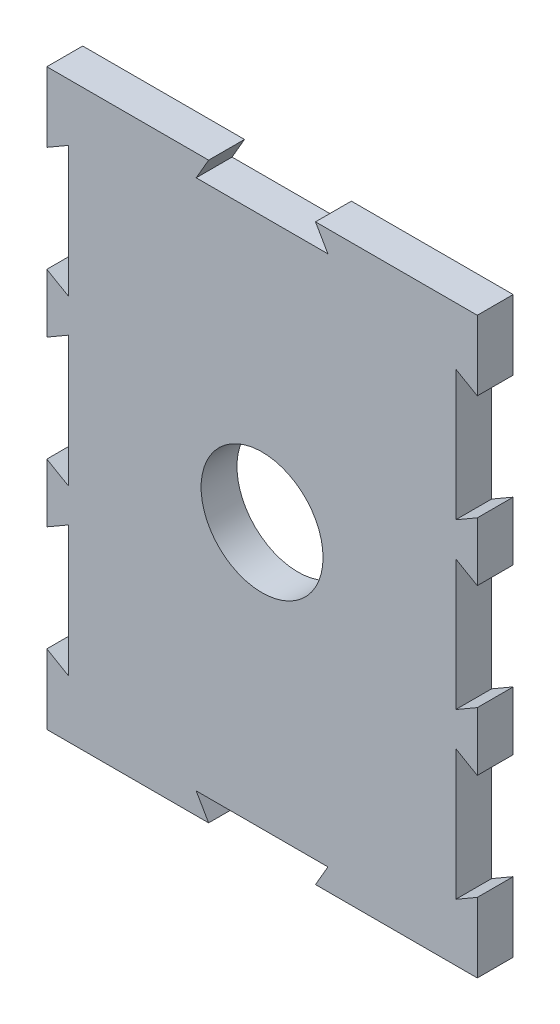
SolidWorks part; units mm, degrees
ref_plane "Front Plane" through (0, 0, 0) normal (1, 0, 0) x (0, 1, 0)
ref_plane "Top Plane" through (0, 0, 0) normal (0, 0, 1) x (0, 1, 0)
ref_plane "Right Plane" through (0, 0, 0) normal (0, 1, 0) x (-1, 0, 0)
sketch "Sketch4" plane through (0, 0, 0) normal (0, 0, 1) x (0, 1, 0)
  line L0 (-22.9067, -42.75) -> (-32, -27)
  line L1 (-40, -30) -> (40, -30)
  line L2 (-40, -30) -> (-40, 30)
  line L3 (-40, 30) -> (40, 30)
  line L4 (40, -30) -> (40, 30)
  line L5 (-40, -30) -> (40, 30) construction
  line L6 (-40, 30) -> (40, -30) construction
  line L7 (-32, -27) -> (-13.8135, -27)
  line L8 (-13.8135, -27) -> (-22.9067, -42.75)
  line L9 (52.9, 0) -> (37, -9.1799)
  line L10 (37, -9.1799) -> (37, 9.1799)
  line L11 (37, 9.1799) -> (52.9, 0)
  line L12 (-55, 0) -> (55, 0) construction
  line L13 (0, -42.75) -> (-9.0933, -27)
  line L14 (9.0933, -27) -> (0, -42.75)
  line L15 (-9.0933, -27) -> (9.0933, -27)
  line L16 (22.9067, -42.75) -> (13.8135, -27)
  line L17 (32, -27) -> (22.9067, -42.75)
  line L18 (13.8135, -27) -> (32, -27)
  line L19 (13.8135, 27) -> (32, 27)
  line L20 (-9.0933, 27) -> (9.0933, 27)
  line L21 (-32, 27) -> (-13.8135, 27)
  line L22 (32, 27) -> (22.9067, 42.75)
  line L23 (22.9067, 42.75) -> (13.8135, 27)
  line L24 (9.0933, 27) -> (0, 42.75)
  line L25 (0, 42.75) -> (-9.0933, 27)
  line L26 (-13.8135, 27) -> (-22.9067, 42.75)
  line L27 (-22.9067, 42.75) -> (-32, 27)
  line L28 (0, -55) -> (0, 55) construction
  line L29 (-37, -9.1799) -> (-37, 9.1799)
  line L30 (-37, 9.1799) -> (-52.9, 0)
  line L31 (-52.9, 0) -> (-37, -9.1799)
  circle A0 centre (0, 0) radius 8.5
  circle A1 centre (-22.9067, -32.25) radius 5.25
  circle A2 centre (42.3, 0) radius 5.3
  circle A3 centre (0, -32.25) radius 5.25
  circle A4 centre (22.9067, -32.25) radius 5.25
  circle A5 centre (22.9067, 32.25) radius 5.25
  circle A6 centre (0, 32.25) radius 5.25
  circle A7 centre (-22.9067, 32.25) radius 5.25
  circle A8 centre (-42.3, 0) radius 5.3
  point P0 (0, 0)
  dimension "D3" = 17
  dimension "D4" = 10.5
  dimension "D5" = 10.6
  dimension "D1" = 80
  dimension "D2" = 60
  dimension "D6" = 0
  dimension "D7" = 3
  dimension "D8" = 3
  dimension "D10" = 8
  dimension "D11" = 8
  dimension "D9" = 3
extrude "Boss-Extrude1" add sketch "Sketch4" along normal blind 5 contours L31 L2 L1 L0 L7 L8 L13 L15 L14 L16 L18 L17 L4 L9 L10 L11 L3 L22 L19 L23 L24 L20 L25 L26 L21 L27 L30 L29 A0
